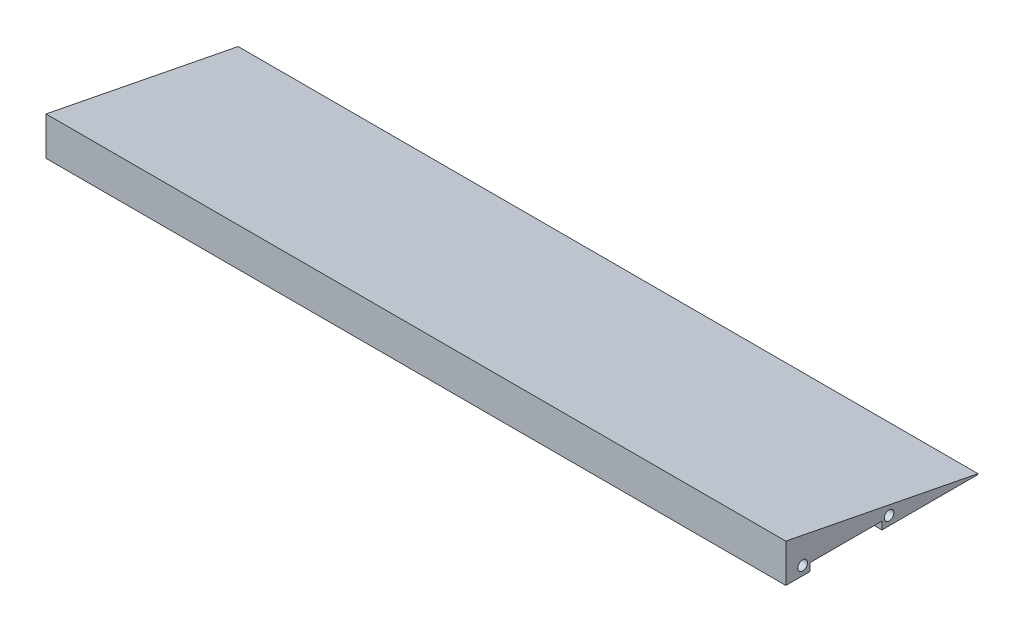
SolidWorks part; units mm, degrees
ref_plane "Front Plane" through (0, 0, 0) normal (0, 0, 1) x (1, 0, 0)
ref_plane "Top Plane" through (0, 0, 0) normal (0, 1, 0) x (1, 0, 0)
ref_plane "Right Plane" through (0, 0, 0) normal (1, 0, 0) x (0, 0, -1)
sketch "Sketch1" plane through (0, 0, 0) normal (1, 0, 0) x (0, 0, -1)
  line L0 (0, 0) -> (0, 20.32)
  line L1 (0, 20.32) -> (101.6, 0.4)
  line L2 (101.6, 0.4) -> (101.6, 0)
  line L3 (101.6, 0) -> (0, 0)
  dimension "D1" = 0.4
  dimension "D2" = 101.6
  dimension "D3" = 20.32
extrude "Boss-Extrude1" add sketch "Sketch1" along normal mid plane 391.16
sketch "Sketch2" plane through (195.58, 0, 0) normal (1, 0, 0) x (0, 0, -1)
  line L0 (0, 0) -> (101.6, 0) construction
  line L1 (101.6, 0.4) -> (0, 20.32) construction
  circle A0 centre (8.8764, 4.7625) radius 2.5527
  circle A1 centre (54.5964, 4.7625) radius 2.5527
  circle A2 centre (54.5964, 4.7625) radius 4.7625 construction
  circle A3 centre (8.8764, 4.7625) radius 4.7625 construction
  dimension "D1" = 45.72
  dimension "D2" = 5.1054
  dimension "D3" = 9.525
extrude "Cut-Extrude1" cut sketch "Sketch2" against normal blind 38.1
mirror "Mirror3" about plane through (0, 0, 0) normal (1, 0, 0) of "Cut-Extrude1"
sketch "Sketch3" plane through (-195.58, 0, 0) normal (-1, 0, 0) x (0, 0, 1)
  line L5 (0, 0) -> (-101.6, 0) construction
  line L6 (-50.8, 4.064) -> (-12.7, 4.064)
  line L7 (-50.8, 4.064) -> (-50.8, 0)
  line L8 (-50.8, 0) -> (-12.7, 0)
  line L9 (-12.7, 4.064) -> (-12.7, 0)
  line L10 (0, 20.32) -> (0, 0) construction
  dimension "D1" = 38.1
  dimension "D2" = 4.064
  dimension "D3" = 0
  dimension "D4" = 12.7
extrude "Cut-Extrude2" cut sketch "Sketch3" against normal through all
sketch "Sketch4" plane through (0, 0, 0) normal (0, -1, 0) x (1, 0, 0)
  line L0 (-144.78, -50.8) -> (-146.1056, -60.2323)
  line L1 (195.58, -50.8) -> (-195.58, -50.8) construction
  line L2 (-144.78, -50.8) -> (-128.3812, -50.8)
  line L5 (-144.78, -50.8) -> (-144.78, -60.2323) construction
  line L6 (-128.3812, -50.8) -> (-127.0556, -60.2323)
  line L7 (-128.3812, -50.8) -> (-128.3812, -60.2323) construction
  line L8 (-144.78, -60.2323) -> (-128.3812, -60.2323)
  line L9 (-144.78, -60.2323) -> (-146.1056, -60.2323)
  line L10 (-128.3812, -60.2323) -> (-127.0556, -60.2323)
  line L11 (-195.58, -50.8) -> (-195.58, -101.6) construction
  line L12 (-77.5812, -50.8) -> (-78.9069, -60.2323)
  line L13 (-77.5812, -60.2323) -> (-78.9069, -60.2323)
  line L14 (-77.5812, -60.2323) -> (-61.1825, -60.2323)
  line L15 (-61.1825, -60.2323) -> (-59.8569, -60.2323)
  line L16 (-61.1825, -50.8) -> (-59.8569, -60.2323)
  line L17 (-77.5812, -50.8) -> (-61.1825, -50.8)
  line L18 (-10.3825, -50.8) -> (-11.7081, -60.2323)
  line L19 (-10.3825, -60.2323) -> (-11.7081, -60.2323)
  line L20 (-10.3825, -60.2323) -> (6.0163, -60.2323)
  line L21 (6.0163, -60.2323) -> (7.3419, -60.2323)
  line L22 (6.0163, -50.8) -> (7.3419, -60.2323)
  line L23 (-10.3825, -50.8) -> (6.0163, -50.8)
  line L24 (56.8163, -50.8) -> (55.4906, -60.2323)
  line L25 (56.8163, -60.2323) -> (55.4906, -60.2323)
  line L26 (56.8163, -60.2323) -> (73.215, -60.2323)
  line L27 (73.215, -60.2323) -> (74.5406, -60.2323)
  line L28 (73.215, -50.8) -> (74.5406, -60.2323)
  line L29 (56.8163, -50.8) -> (73.215, -50.8)
  line L30 (124.015, -50.8) -> (122.6894, -60.2323)
  line L31 (124.015, -60.2323) -> (122.6894, -60.2323)
  line L32 (124.015, -60.2323) -> (140.4138, -60.2323)
  line L33 (140.4138, -60.2323) -> (141.7394, -60.2323)
  line L34 (140.4138, -50.8) -> (141.7394, -60.2323)
  line L35 (124.015, -50.8) -> (140.4138, -50.8)
  line L42 (-195.58, -31.75) -> (195.58, -31.75) construction
  line L43 (-195.58, -12.7) -> (-195.58, -50.8) construction
  line L44 (195.58, -12.7) -> (195.58, -50.8) construction
  line L52 (124.015, -12.7) -> (140.4138, -12.7)
  line L53 (140.4138, -12.7) -> (141.7394, -3.2677)
  line L54 (140.4138, -3.2677) -> (141.7394, -3.2677)
  line L55 (124.015, -3.2677) -> (140.4138, -3.2677)
  line L56 (124.015, -3.2677) -> (122.6894, -3.2677)
  line L57 (124.015, -12.7) -> (122.6894, -3.2677)
  line L58 (56.8163, -12.7) -> (73.215, -12.7)
  line L59 (73.215, -12.7) -> (74.5406, -3.2677)
  line L60 (73.215, -3.2677) -> (74.5406, -3.2677)
  line L61 (56.8163, -3.2677) -> (73.215, -3.2677)
  line L62 (56.8163, -3.2677) -> (55.4906, -3.2677)
  line L63 (56.8163, -12.7) -> (55.4906, -3.2677)
  line L64 (-10.3825, -12.7) -> (6.0163, -12.7)
  line L65 (6.0163, -12.7) -> (7.3419, -3.2677)
  line L66 (6.0163, -3.2677) -> (7.3419, -3.2677)
  line L67 (-10.3825, -3.2677) -> (6.0163, -3.2677)
  line L68 (-10.3825, -3.2677) -> (-11.7081, -3.2677)
  line L69 (-10.3825, -12.7) -> (-11.7081, -3.2677)
  line L70 (-77.5812, -12.7) -> (-61.1825, -12.7)
  line L71 (-61.1825, -12.7) -> (-59.8569, -3.2677)
  line L72 (-61.1825, -3.2677) -> (-59.8569, -3.2677)
  line L73 (-77.5812, -3.2677) -> (-61.1825, -3.2677)
  line L74 (-77.5812, -3.2677) -> (-78.9069, -3.2677)
  line L75 (-77.5812, -12.7) -> (-78.9069, -3.2677)
  line L76 (-144.78, -12.7) -> (-128.3812, -12.7)
  line L77 (-128.3812, -12.7) -> (-127.0556, -3.2677)
  line L78 (-128.3812, -3.2677) -> (-127.0556, -3.2677)
  line L79 (-144.78, -3.2677) -> (-128.3812, -3.2677)
  line L80 (-144.78, -3.2677) -> (-146.1056, -3.2677)
  line L81 (-144.78, -12.7) -> (-146.1056, -3.2677)
  dimension "D1" = 8
  dimension "D2" = 8
  dimension "D3" = 19.05
  dimension "D4" = 9.525
  dimension "D5" = 50.8
  dimension "D7" = 50.8
  dimension "D6" = 5
extrude "Cut-Extrude3" cut sketch "Sketch4" against normal blind 4.064
